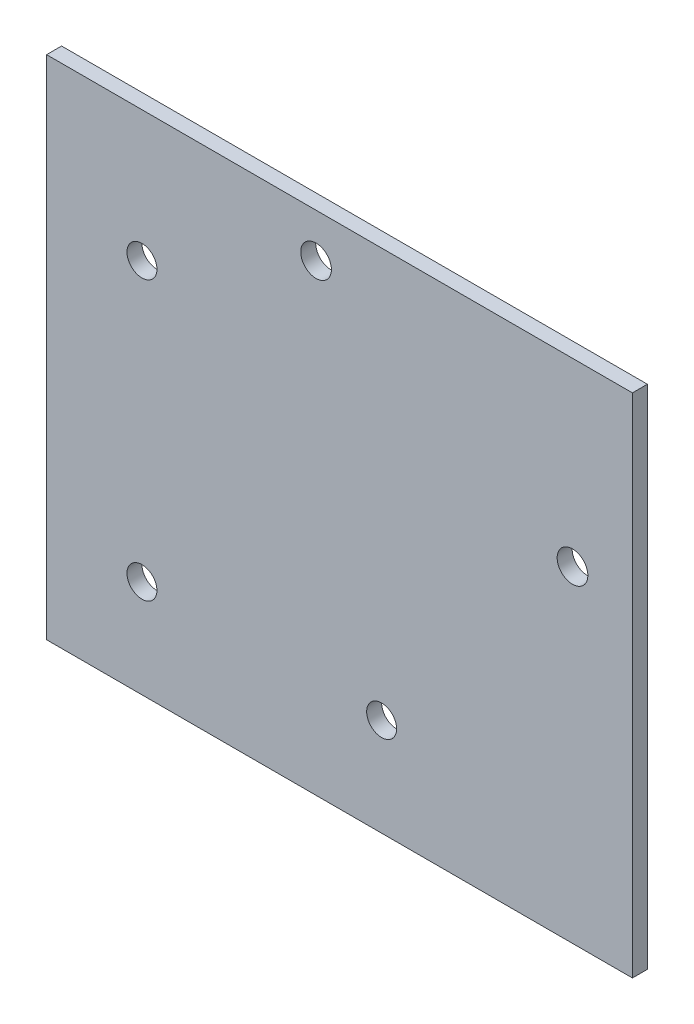
SolidWorks part; units mm, degrees
ref_plane "Front Plane" through (0, 0, 0) normal (0, 0, 1) x (1, 0, 0)
ref_plane "Top Plane" through (0, 0, 0) normal (0, 1, 0) x (1, 0, 0)
ref_plane "Right Plane" through (0, 0, 0) normal (1, 0, 0) x (0, 0, -1)
sketch "Sketch1" plane through (0, 0, 0) normal (0, 0, 1) x (1, 0, 0)
  line L0 (100.4021, 128.27) -> (100.4021, 179.07) construction
  line L1 (129.3581, 204.6053) -> (5.1872, 204.6053)
  line L2 (129.3581, 204.6053) -> (129.3581, 97.1939)
  line L3 (129.3581, 97.1939) -> (5.1872, 97.1939)
  line L4 (5.1872, 204.6053) -> (5.1872, 97.1939)
  line L5 (100.4021, 179.07) -> (49.6021, 179.07) construction
  line L6 (49.6021, 179.07) -> (49.6021, 128.27) construction
  circle A0 centre (25.4, 117.9286) radius 3.175
  circle A1 centre (25.4, 176.8929) radius 3.175
  circle A2 centre (76.2, 117.9286) radius 3.175
  circle A3 centre (116.6581, 166.37) radius 3.2512
  circle A4 centre (62.3021, 195.326) radius 3.2512
  point P17 (104.9594, 166.37)
  dimension "D1" = 6.35
  dimension "D4" = 6.5024
  dimension "D2" = 20.7346
  dimension "D3" = 20.2128
  dimension "D6" = 12.7
  dimension "D7" = 16.256
  dimension "D8" = 12.7
  dimension "D10" = 38.2353
  dimension "D5" = 16.256
  dimension "D9" = 12.7
extrude "Boss-Extrude1" add sketch "Sketch1" along normal blind 3.175
equation "\"80/20 to Center Hole\"= .64in"
equation "\"80/20 from Edge\"= 0.5in"
equation "\"D6@Sketch1\"=\"80/20 from Edge\""
equation "\"D8@Sketch1\"=\"80/20 from Edge\""
equation "\"D7@Sketch1\"=\"80/20 to Center Hole\""
equation "\"D5@Sketch1\"=\"80/20 to Center Hole\""
